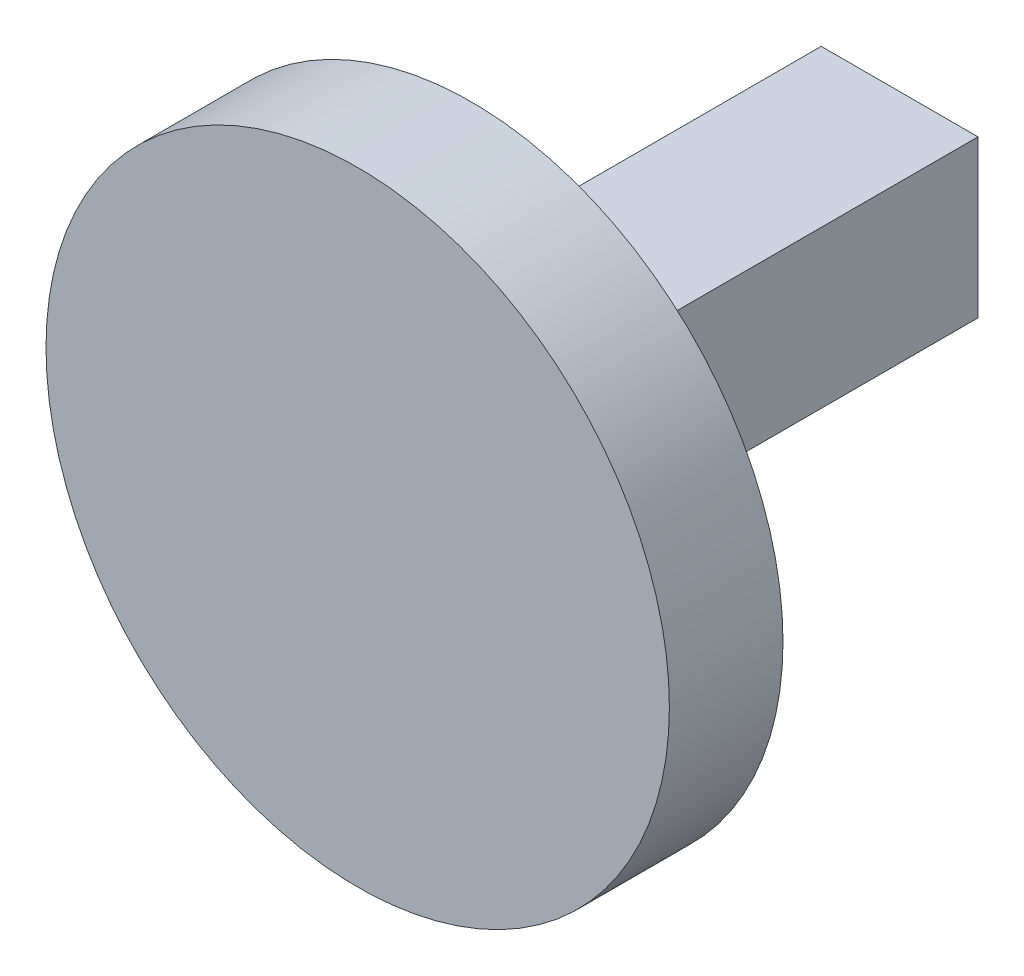
SolidWorks part; units mm, degrees
ref_plane "Front Plane" through (0, 0, 0) normal (0, 0, 1) x (1, 0, 0)
ref_plane "Top Plane" through (0, 0, 0) normal (0, 1, 0) x (1, 0, 0)
ref_plane "Right Plane" through (0, 0, 0) normal (1, 0, 0) x (0, 0, -1)
sketch "Sketch1" plane through (0, 0, 0) normal (0, 0, 1) x (1, 0, 0)
  circle A0 centre (1.1501, -20.0814) radius 13.7179
extrude "Boss-Extrude1" add sketch "Sketch1" against normal blind 5 from offset 5 offset against normal yes
sketch "Sketch2" plane through (0, 0, -10) normal (0, 0, -1) x (-1, 0, 0)
  line L0 (4.25, -27.5) -> (-7.5, -27.5) construction
  line L1 (-3.45, -16.55) -> (3.45, -16.55)
  line L2 (-3.45, -16.55) -> (-3.45, -23.45)
  line L3 (-3.45, -23.45) -> (3.45, -23.45)
  line L4 (3.45, -16.55) -> (3.45, -23.45)
  line L5 (-3.45, -16.55) -> (3.45, -23.45) construction
  line L6 (-3.45, -23.45) -> (3.45, -16.55) construction
  line L7 (-7.5, -27.5) -> (-7.5, 7.5) construction
  point P0 (0, -20)
  dimension "D1" = 6.9
  dimension "D2" = 6.9
  dimension "D3" = 7.5
  dimension "D4" = 7.5
extrude "Boss-Extrude2" add sketch "Sketch2" along normal blind 20
